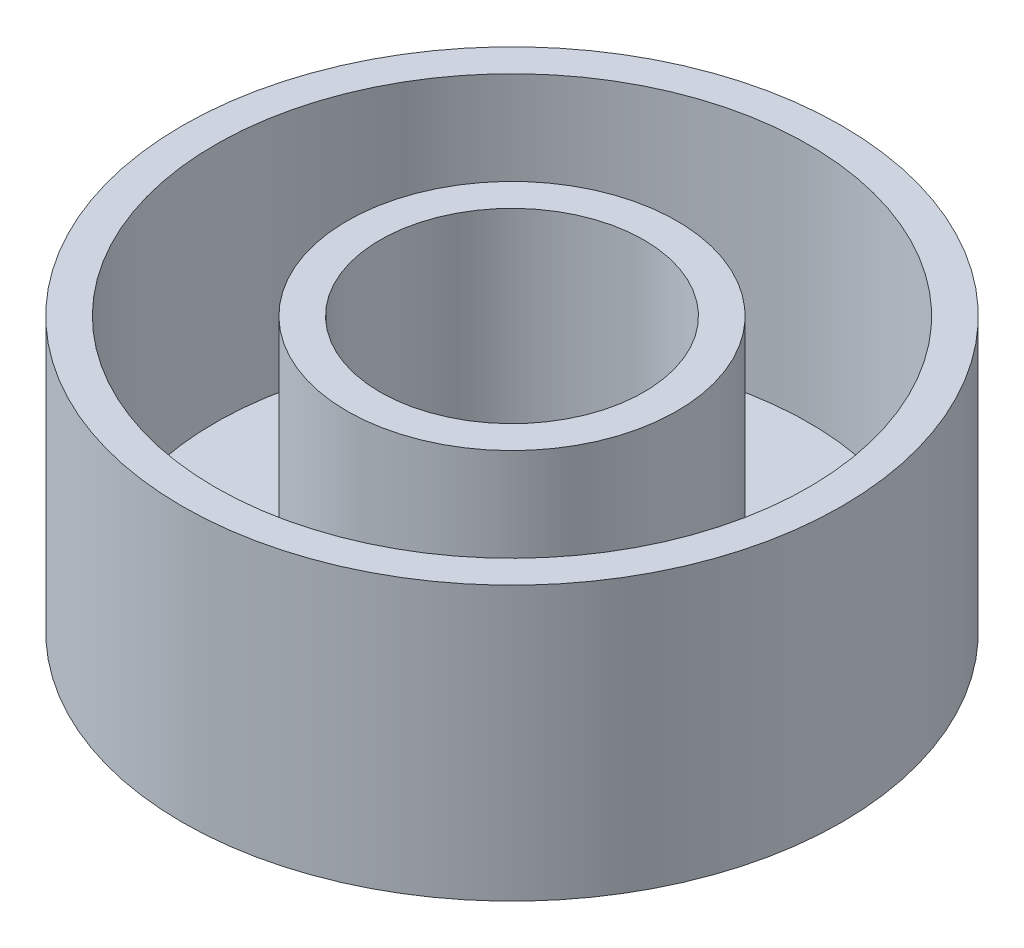
SolidWorks part; units mm, degrees
material "VITON"
ref_plane "Front Plane" through (0, 0, 0) normal (0, 0, 1) x (1, 0, 0)
ref_plane "Top Plane" through (0, 0, 0) normal (0, 1, 0) x (1, 0, 0)
ref_plane "Right Plane" through (0, 0, 0) normal (1, 0, 0) x (0, 0, -1)
sketch "Sketch1" plane through (0, 0, 0) normal (0, 1, 0) x (1, 0, 0)
  circle A0 centre (0, 0) radius 10
  dimension "D1" = 20
extrude "main extrusion" add sketch "Sketch1" along normal blind 8.3 contours A0
sketch "Sketch2" plane through (0, 8.3, 0) normal (0, 1, 0) x (1, 0, 0)
  circle A0 centre (0, 0) radius 4
  dimension "D1" = 8
extrude "ID bore" cut sketch "Sketch2" against normal blind 20
sketch "Sketch3" plane through (0, 8.3, 0) normal (0, 1, 0) x (1, 0, 0)
  circle A0 centre (0, 0) radius 9
  circle A1 centre (0, 0) radius 5
  dimension "D1" = 10
  dimension "D2" = 18
extrude "seal recess" cut sketch "Sketch3" against normal blind 7.3
equation "\"D1@Sketch1\" = \"small seal OD\""
equation "\"D1@main extrusion\" = \"small seal depth\""
equation "\"D1@Sketch2\"= \"small seal ID\""
equation "\"motor mount pattern diameter\"= 30mm"
equation "\"D2@Sketch3\" = \"small seal OD\" - 2mm"
equation "\"D1@Sketch3\" = \"small seal ID\" + 2mm"
equation "\"D1@seal recess\" = \"small seal depth\" - 1mm"
equation "\"bearing OD\"= 30mm"
equation "\"bearing outer race thickness\"= 1mm"
equation "\"bearing ID\"= 10mm"
equation "\"bearing depth\"= 9mm"
equation "\"bearing inner race thickness\"= 1mm"
equation "\"small seal OD\"= 20mm"
equation "\"small seal ID\"= 8mm"
equation "\"small seal depth\"= 8.3mm"
equation "\"big seal OD\"= 27mm"
